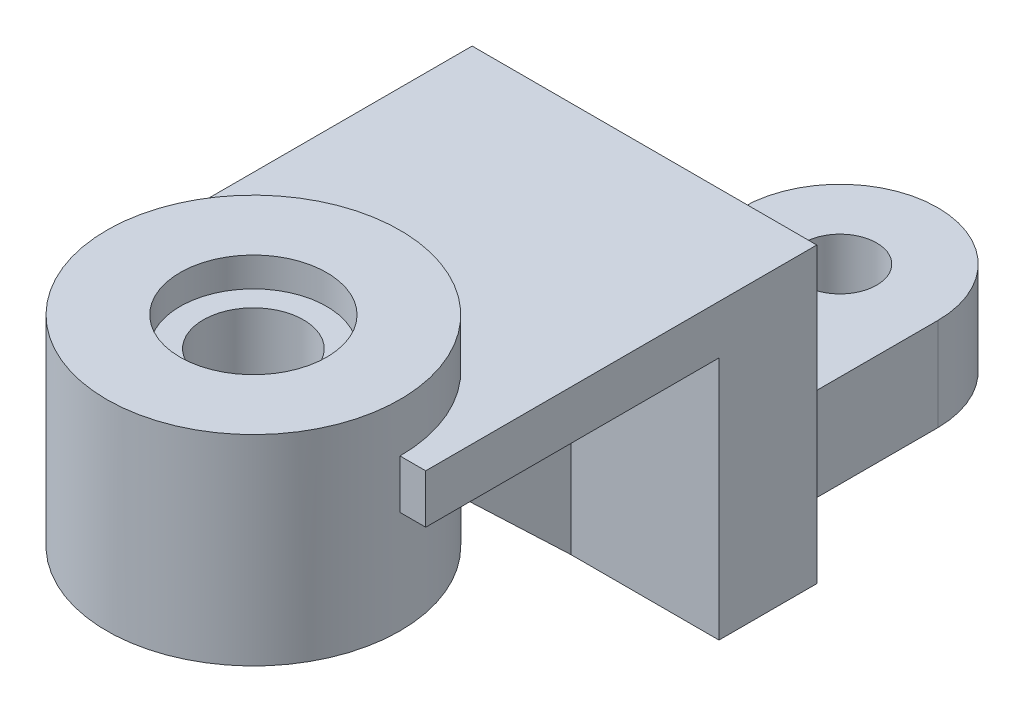
SolidWorks part; units mm, degrees
ref_plane "Front Plane" through (0, 0, 0) normal (0, 0, 1) x (1, 0, 0)
ref_plane "Top Plane" through (0, 0, 0) normal (0, 1, 0) x (1, 0, 0)
ref_plane "Right Plane" through (0, 0, 0) normal (1, 0, 0) x (0, 0, -1)
sketch "Sketch1" plane through (0, 0, 0) normal (0, 1, 0) x (1, 0, 0)
  line L0 (-20, 0) -> (-20, -40)
  line L1 (-20, -40) -> (20, -40)
  line L2 (20, -40) -> (20, 0)
  arc A0 (20, 0) -> (-20, 0) centre (0, 0) ccw
  dimension "D1" = 40
  dimension "D2" = 40
extrude "Boss-Extrude1" add sketch "Sketch1" along normal blind 19 contours A0 L0 L1 L2
sketch "Sketch3" plane through (0, 0, 0) normal (0, 1, 0) x (1, 0, 0)
  line L0 (0, -40) -> (35.25, -40)
  line L1 (-20, -40) -> (20, -40) construction
  line L2 (35.25, -40) -> (35.25, -60)
  line L3 (35.25, -60) -> (-35.25, -60)
  line L4 (-35.25, -60) -> (-35.25, -40)
  line L5 (-35.25, -40) -> (0, -40)
  dimension "D1" = 35.25
  dimension "D2" = 20
  dimension "D3" = 70.5
extrude "Boss-Extrude3" add sketch "Sketch3" along normal blind 60
fillet "Fillet1" radius 10 1 edges at (20, 9.5, 40)
fillet "Fillet2" radius 10 1 edges at (-20, 9.5, 40)
sketch "Sketch4" plane through (0, 0, 0) normal (0, -1, 0) x (1, 0, 0)
  circle A0 centre (0, 0) radius 7.5
  dimension "D1" = 15
extrude "Cut-Extrude1" cut sketch "Sketch4" against normal blind 60
sketch "Sketch6" plane through (35.25, 0, 0) normal (1, 0, 0) x (0, 0, -1)
  line L0 (-60, 60) -> (-120, 60)
  line L1 (-120, 60) -> (-120, 50)
  line L2 (-120, 50) -> (-60, 50)
  line L3 (-60, 60) -> (-60, 0) construction
  line L4 (-60, 50) -> (-60, 60)
  dimension "D1" = 80
  dimension "D2" = 10
extrude "Boss-Extrude4" add sketch "Sketch6" against normal blind 70.5
sketch "Sketch7" plane through (0, 60, 0) normal (0, 1, 0) x (1, 0, 0)
  line L0 (-30, -120) -> (30, -120)
  line L1 (-35.25, -120) -> (35.25, -120) construction
  arc A0 (30, -120) -> (-30, -120) centre (0, -120) ccw
  dimension "D1" = 60
extrude "Cut-Extrude2" cut sketch "Sketch7" against normal blind 70.5
sketch "Sketch8" plane through (0, 60, 0) normal (0, 1, 0) x (1, 0, 0)
  circle A0 centre (0, -120) radius 30
extrude "Boss-Extrude6" add sketch "Sketch8" against normal blind 31 and the other way blind 10 contours A0
sketch "Sketch10" plane through (0, 70, 0) normal (0, 1, 0) x (1, 0, 0)
  circle A0 centre (0, -120) radius 10.25
  dimension "D1" = 20.5
extrude "Cut-Extrude3" cut sketch "Sketch10" against normal blind 41
sketch "Sketch11" plane through (0, 70, 0) normal (0, 1, 0) x (1, 0, 0)
  circle A0 centre (0, -120) radius 15
  dimension "D1" = 30
extrude "Cut-Extrude4" cut sketch "Sketch11" against normal blind 6
sketch "Sketch12" plane through (0, 29, 0) normal (0, -1, 0) x (1, 0, 0)
  circle A0 centre (0, 120) radius 15
  dimension "D1" = 30
extrude "Cut-Extrude5" cut sketch "Sketch12" against normal blind 6
sketch "Sketch13" plane through (0, 29, 0) normal (0, -1, 0) x (1, 0, 0)
  line L0 (-5, 90.4196) -> (5, 90.4196)
  line L1 (5, 60) -> (5, 90.4196)
  line L2 (-5, 60) -> (-5, 90.4196)
  line L3 (-5, 60) -> (5, 60)
  arc A0 (-30, 120) -> (30, 120) centre (0, 120) ccw construction
  circle A1 centre (0, 120) radius 30 construction
  circle A2 centre (0, 120) radius 15 construction
  dimension "D1" = 5
  dimension "D2" = 60
extrude "Boss-Extrude7" add sketch "Sketch13" against normal blind 30
sketch "Sketch16" plane through (5, 0, 0) normal (1, 0, 0) x (0, 0, -1)
  line L0 (-90.4196, 29) -> (-60, 29)
  line L1 (-60, 29) -> (-60, 0)
  line L2 (-60, 0) -> (-90.4196, 29)
extrude "Boss-Extrude8" add sketch "Sketch16" against normal blind 10
